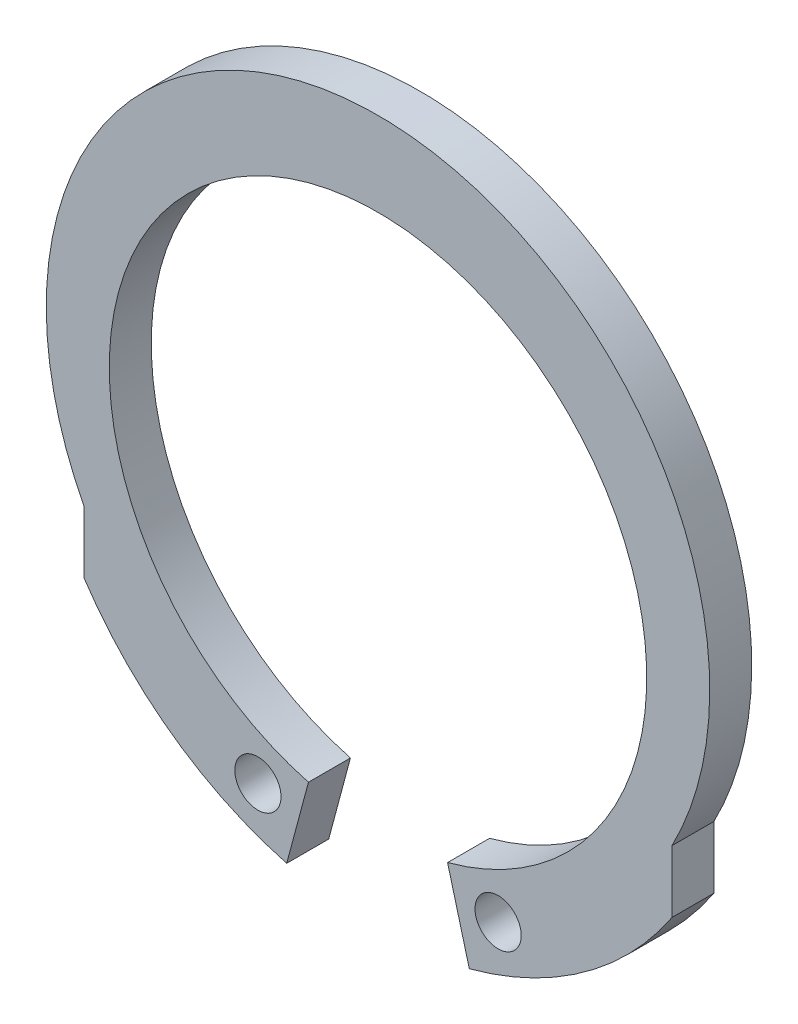
SolidWorks part; units mm, degrees
ref_plane "Front Plane" through (0, 0, 0) normal (0, 0, 1) x (1, 0, 0)
ref_plane "Top Plane" through (0, 0, 0) normal (0, 1, 0) x (1, 0, 0)
ref_plane "Right Plane" through (0, 0, 0) normal (1, 0, 0) x (0, 0, -1)
sketch "Sketch1" plane through (0, 0, 0) normal (0, 0, 1) x (1, 0, 0)
  line L0 (1.6564, -6.1819) -> (2.1741, -8.1138)
  line L1 (0, 0) -> (0, -12.8991) construction
  line L2 (-2.1741, -8.1138) -> (-1.6564, -6.1819)
  line L3 (-7, -4.6433) -> (-7, -3.162)
  line L4 (7, -4.6433) -> (7, -3.162)
  arc A0 (1.6564, -6.1819) -> (-1.6564, -6.1819) centre (0, 0) ccw
  arc A1 (2.1741, -8.1138) -> (7, -4.6433) centre (0, 0) ccw
  arc A2 (7, -3.162) -> (-7, -3.162) centre (0, 0.5) ccw
  arc A3 (-7, -4.6433) -> (-2.1741, -8.1138) centre (0, 0) ccw
  circle A4 centre (-2.86, -6.81) radius 0.55
  circle A5 centre (0, 0) radius 8.4 construction
  circle A6 centre (2.86, -6.81) radius 0.55
  dimension "D1" = 12.8
  dimension "D2" = 2
  dimension "D6" = 7.9
  dimension "D7" = 1.1
  dimension "D9" = 16.8
  dimension "D10" = 2.86
  dimension "D3" = 15
  dimension "D4" = 15
  dimension "D5" = 7
  dimension "D8" = 1
extrude "Extrude1" add sketch "Sketch1" along normal blind 1
